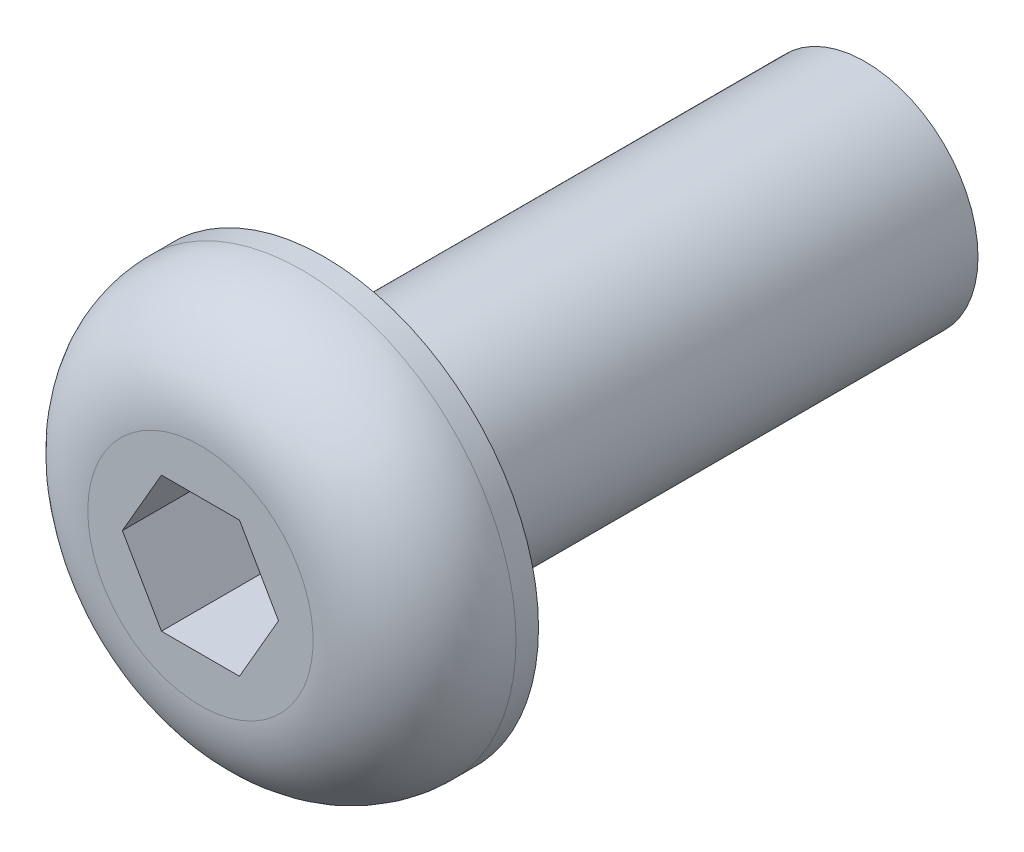
SolidWorks part; units mm, degrees
material "AISI 304"
ref_plane "Front Plane" through (0, 0, 0) normal (0, 0, 1) x (1, 0, 0)
ref_plane "Top Plane" through (0, 0, 0) normal (0, 1, 0) x (1, 0, 0)
ref_plane "Right Plane" through (0, 0, 0) normal (1, 0, 0) x (0, 0, -1)
sketch "Sketch1" plane through (0, 0, 0) normal (0, 0, 1) x (1, 0, 0)
  circle A0 centre (0, 0) radius 2.5
  dimension "D1" = 5
extrude "Extrude1" add sketch "Sketch1" against normal blind 12
sketch "Sketch2" plane through (0, 0, 0) normal (1, 0, 0) x (0, 0, -1)
  line L0 (0, 0) -> (-10.9859, 0) construction
  line L1 (0, 0) -> (0, 4.75)
  line L2 (0, 4.75) -> (-0.5, 4.75)
  line L3 (-2.75, 0) -> (-2.75, 2.5)
  line L4 (0, 0) -> (-2.75, 0)
  arc A0 (-2.75, 2.5) -> (-0.5, 4.75) centre (-0.5, 2.5) cw
  dimension "D1" = 2.75
  dimension "D2" = 9.5
  dimension "D3" = 0.5
revolve "Revolve1" add sketch "Sketch2" angle 360 about L0
sketch "Sketch3" plane through (0, 0, 2.75) normal (0, 0, 1) x (1, 0, 0)
  line L1 (-0.866, 1.5) -> (-1.7321, 0)
  line L2 (-1.7321, 0) -> (-0.866, -1.5)
  line L3 (-0.866, -1.5) -> (0.866, -1.5)
  line L4 (0.866, -1.5) -> (1.7321, 0)
  line L5 (1.7321, 0) -> (0.866, 1.5)
  line L6 (0.866, 1.5) -> (-0.866, 1.5)
  circle A0 centre (0, 0) radius 1.5 construction
  dimension "D1" = 3
extrude "Cut-Extrude1" cut sketch "Sketch3" against normal blind 2.5
